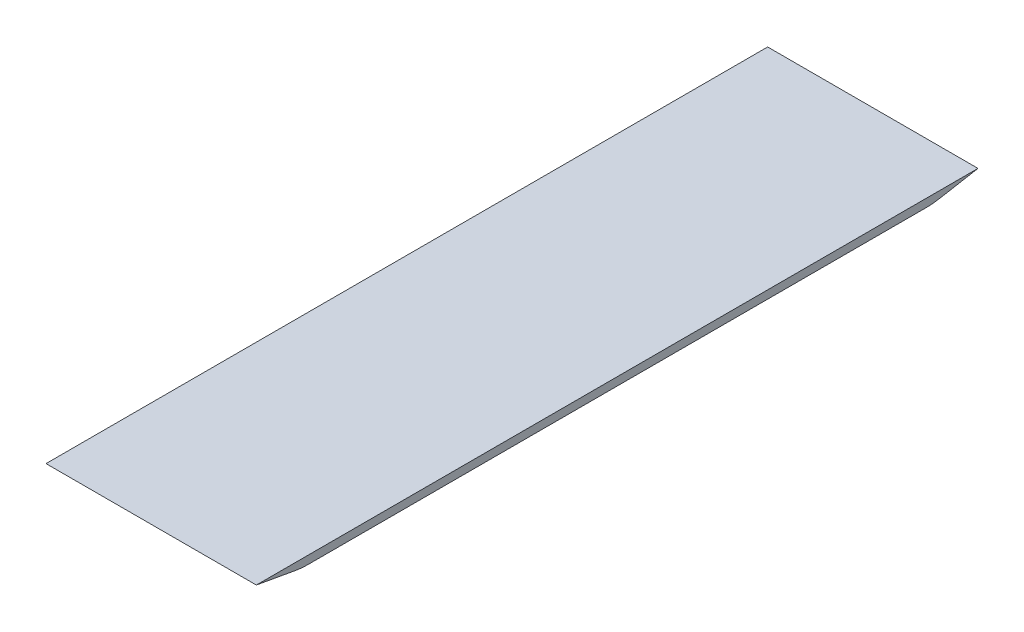
SolidWorks part; units mm, degrees
ref_plane "Front Plane" through (0, 0, 0) normal (0, 0, 1) x (1, 0, 0)
ref_plane "Top Plane" through (0, 0, 0) normal (0, 1, 0) x (1, 0, 0)
ref_plane "Right Plane" through (0, 0, 0) normal (1, 0, 0) x (0, 0, -1)
sketch "Sketch1" plane through (0, 0, 0) normal (1, 0, 0) x (0, 0, -1)
  line L0 (0, 0) -> (446, 0)
  line L1 (446, 0) -> (418, -5)
  line L2 (418, -5) -> (28, -5)
  line L3 (28, -5) -> (0, 0)
  dimension "D1" = 390
  dimension "D2" = 28
  dimension "D3" = 28
  dimension "D4" = 5
extrude "Boss-Extrude1" add sketch "Sketch1" along normal blind 130 contours L2 L3 L0 L1
fillet "Fillet1" radius 50 2 edges at (65, -5, -28) (65, -5, -418)
